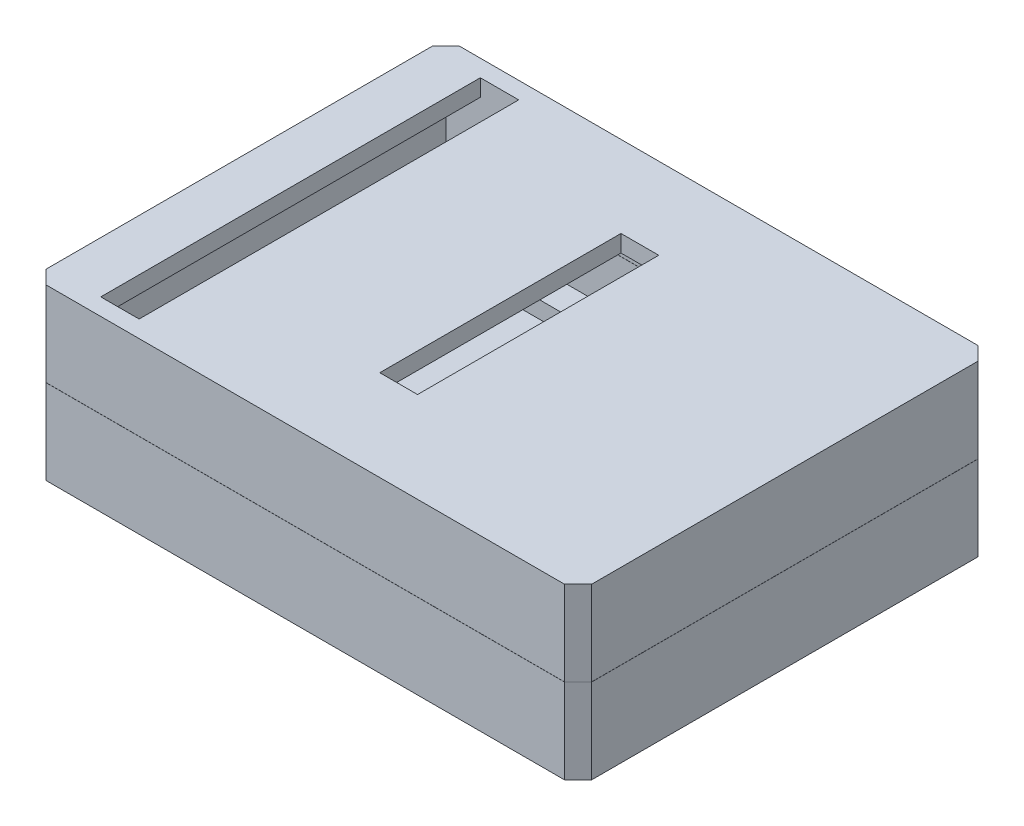
SolidWorks part; units mm, degrees
ref_plane "Front Plane" through (0, 0, 0) normal (0, 0, 1) x (1, 0, 0)
ref_plane "Top Plane" through (0, 0, 0) normal (0, 1, 0) x (1, 0, 0)
ref_plane "Right Plane" through (0, 0, 0) normal (1, 0, 0) x (0, 0, -1)
sketch "Sketch1" plane through (0, 0, 0) normal (0, 1, 0) x (1, 0, 0)
  line L1 (-51.1175, -38.735) -> (51.1175, -38.735)
  line L2 (-51.1175, -38.735) -> (-51.1175, 38.735)
  line L3 (-51.1175, 38.735) -> (51.1175, 38.735)
  line L4 (51.1175, -38.735) -> (51.1175, 38.735)
  line L5 (-51.1175, -38.735) -> (51.1175, 38.735) construction
  line L6 (-51.1175, 38.735) -> (51.1175, -38.735) construction
  point P0 (0, 0)
  dimension "D1" = 102.235
  dimension "D2" = 77.47
extrude "Boss-Extrude1" add sketch "Sketch1" along normal blind 31.75 contours L2 L3 L4 L1
sketch "Sketch5" plane through (0, 0, 38.735) normal (0, 0, 1) x (1, 0, 0)
  line L1 (-70.7849, 15.875) -> (67.3001, 15.875)
  line L2 (-70.7849, 15.875) -> (-70.7849, 15.9004)
  line L3 (-70.7849, 15.9004) -> (67.3001, 15.9004)
  line L4 (67.3001, 15.875) -> (67.3001, 15.9004)
  line L5 (-51.1175, 31.75) -> (-51.1175, 0) construction
  point P7 (-51.1175, 15.875)
  dimension "D1" = 0.0254
extrude "Cut-Extrude4" cut sketch "Sketch5" against normal through all
shell "Shell1" thickness 3.175
shell "Shell2" thickness 3.175
sketch "Sketch6" plane through (0, 3.175, 0) normal (0, 1, 0) x (1, 0, 0)
  line L0 (-47.9425, 35.56) -> (47.9425, 35.56)
  line L1 (47.9425, 35.56) -> (47.9425, -35.56)
  line L2 (47.9425, -35.56) -> (-47.9425, -35.56)
  line L3 (-47.9425, -35.56) -> (-47.9425, 35.56)
  line L4 (-42.8625, -30.48) -> (-42.8625, 30.48)
  line L5 (-42.8625, 30.48) -> (42.8625, 30.48)
  line L7 (42.8625, -30.48) -> (-42.8625, -30.48)
  line L13 (42.8625, 30.48) -> (42.8625, -30.48)
  line L14 (-47.9425, 35.56) -> (47.9425, 35.56) construction
  line L15 (-47.9425, -35.56) -> (-47.9425, 35.56) construction
  dimension "D1" = 5.08
  dimension "D2" = 5.08
  dimension "D3" = 5.08
  dimension "D4" = 5.08
extrude "Boss-Extrude2" add sketch "Sketch6" along normal blind 3.175
sketch "Sketch7" plane through (0, 6.35, 0) normal (0, 1, 0) x (1, 0, 0)
  line L0 (42.8625, 30.48) -> (-42.8625, 30.48) construction
  line L1 (-42.8625, 30.48) -> (-30.4835, 30.48)
  line L2 (-42.8625, 30.48) -> (-42.8625, 35.56)
  line L3 (-42.8625, 35.56) -> (-30.4835, 35.56)
  line L4 (-30.4835, 30.48) -> (-30.4835, 35.56)
  line L5 (-42.8625, 30.48) -> (-42.8625, -30.48) construction
  line L6 (-47.9425, 35.56) -> (47.9425, 35.56) construction
  line L7 (-42.8625, -30.48) -> (42.8625, -30.48) construction
  line L8 (-42.8625, -30.48) -> (-30.4835, -30.48)
  line L9 (-42.8625, -30.48) -> (-42.8625, -35.56)
  line L10 (-42.8625, -35.56) -> (-30.4835, -35.56)
  line L11 (-30.4835, -30.48) -> (-30.4835, -35.56)
  line L12 (-47.9425, -35.56) -> (47.9425, -35.56) construction
extrude "Cut-Extrude5" cut sketch "Sketch7" against normal up to surface (3.175 mm away) up to face at (0, 3.175, 0)
sketch "Sketch8" plane through (0, 28.575, 0) normal (0, -1, 0) x (1, 0, 0)
  line L0 (47.9425, 35.56) -> (-47.9425, 35.56) construction
  line L1 (-41.4908, 35.56) -> (-34.3034, 35.56)
  line L2 (-41.4908, 35.56) -> (-41.4908, -35.56)
  line L3 (-41.4908, -35.56) -> (-34.3034, -35.56)
  line L4 (-34.3034, 35.56) -> (-34.3034, -35.56)
  line L5 (47.9425, -35.56) -> (-47.9425, -35.56) construction
  line L7 (-3.0492, 21.7255) -> (4.0293, 21.7255)
  line L8 (-3.0492, 21.7255) -> (-3.0492, -23.4679)
  line L9 (-3.0492, -23.4679) -> (4.0293, -23.4679)
  line L10 (4.0293, 21.7255) -> (4.0293, -23.4679)
extrude "Cut-Extrude6" cut sketch "Sketch8" against normal through all
chamfer "Chamfer1" distance 2.54 angle 45 4 edges at (-51.1175, 23.8252, -38.735) (51.1175, 23.8252, -38.735) (51.1175, 23.8252, 38.735) (-51.1175, 23.8252, 38.735)
chamfer "Chamfer2" distance 2.54 angle 45 4 edges at (51.1175, 7.9375, -38.735) (51.1175, 7.9375, 38.735) (-51.1175, 7.9375, 38.735) (-51.1175, 7.9375, -38.735)
sketch "Sketch9" plane through (0, 3.175, 0) normal (0, 1, 0) x (1, 0, 0)
  line L0 (-42.8625, 35.56) -> (-42.8625, -35.56) construction
  line L1 (42.8625, 30.48) -> (-30.4835, 30.48) construction
  line L2 (42.8625, -30.48) -> (42.8625, 30.48) construction
  line L4 (-30.4835, -30.48) -> (42.8625, -30.48) construction
  circle A0 centre (-39.6875, 27.305) radius 3.175
  circle A1 centre (39.6875, 27.305) radius 3.175
  circle A2 centre (39.6875, -27.305) radius 3.175
  circle A3 centre (-39.6875, -27.305) radius 3.175
  dimension "D1" = 6.35
extrude "Cut-Extrude7" cut sketch "Sketch9" against normal through all
equation "\"wallThickness\"= 1 / 8in"
equation "\"D1@Sketch1\"=1.4in+2.25+.125+2*\"wallThickness\""
equation "\"D2@Sketch1\"=2.8in+2*\"wallThickness\""
equation "\"D1@Shell1\"= \"wallThickness\""
equation "\"D1@Shell2\" = \"wallThickness\""
